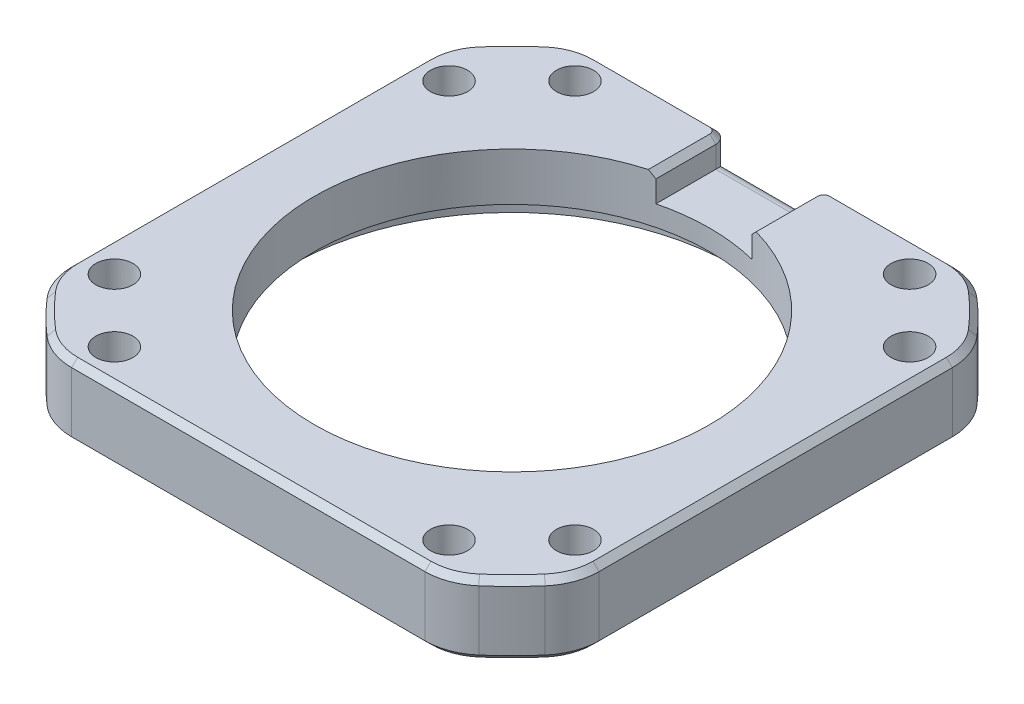
SolidWorks part; units mm, degrees
material "6061 合金"
ref_plane "前视基准面" through (0, 0, 0) normal (0, 0, 1) x (1, 0, 0)
ref_plane "上视基准面" through (0, 0, 0) normal (0, 1, 0) x (1, 0, 0)
ref_plane "右视基准面" through (0, 0, 0) normal (1, 0, 0) x (0, 0, -1)
sketch "草图1" plane through (0, 0, 0) normal (0, 1, 0) x (1, 0, 0)
  line L0 (-16.5, 22) -> (16.5, 22)
  line L1 (-22, 16.5) -> (-22, -16.5)
  line L2 (-16.5, -22) -> (16.5, -22)
  line L3 (22, 16.5) -> (22, -16.5)
  arc A24 (-16.5, 22) -> (-22, 16.5) centre (0, 0) ccw
  arc A25 (22, 16.5) -> (16.5, 22) centre (0, 0) ccw
  arc A26 (16.5, -22) -> (22, -16.5) centre (0, 0) ccw
  arc A27 (-22, -16.5) -> (-16.5, -22) centre (0, 0) ccw
  dimension "D1" = 55
  dimension "D2" = 22
  dimension "D3" = 22
  dimension "D4" = 22
  dimension "D5" = 22
extrude "凸台-拉伸1" add sketch "草图1" along normal blind 6
sketch "草图2" plane through (0, 6, 0) normal (0, 1, 0) x (1, 0, 0)
  circle A0 centre (0, 0) radius 10.5
  dimension "D1" = 21
extrude "切除-拉伸1" cut sketch "草图2" against normal blind 10
sketch "草图3" plane through (0, 6, 0) normal (0, 1, 0) x (1, 0, 0)
  line L0 (-19.2142, 13.9599) -> (0, 0) construction
  line L1 (0, 0) -> (-23.75, 0) construction
  line L2 (0, 0) -> (-16.7938, 16.7938) construction
  line L3 (0, 23.75) -> (0, 0) construction
  circle A0 centre (0, 0) radius 23.75 construction
  circle A1 centre (-19.2142, 13.9599) radius 1.55
  circle A2 centre (-13.9599, 19.2142) radius 1.55
  circle A3 centre (19.2142, 13.9599) radius 1.55
  circle A4 centre (13.9599, 19.2142) radius 1.55
  circle A5 centre (19.2142, -13.9599) radius 1.55
  circle A6 centre (13.9599, -19.2142) radius 1.55
  circle A7 centre (-19.2142, -13.9599) radius 1.55
  circle A8 centre (-13.9599, -19.2142) radius 1.55
  dimension "D1" = 47.5
  dimension "D3" = 3.1
  dimension "D2" = 36
  dimension "D4" = 45
extrude "切除-拉伸2" cut sketch "草图3" against normal blind 10
sketch "草图4" plane through (0, 6, 0) normal (0, 1, 0) x (1, 0, 0)
  circle B0 centre (18.6877, 26.5899) radius 1.55
  circle B1 centre (26.5899, 18.6877) radius 1.55
  circle B2 centre (26.5899, -18.6877) radius 1.55
  circle B3 centre (18.6877, -26.5899) radius 1.55
  circle B4 centre (-18.6877, -26.5899) radius 1.55
  circle B5 centre (-26.5899, -18.6877) radius 1.55
  circle B6 centre (-26.5899, 18.6877) radius 1.55
  circle B7 centre (-18.6877, 26.5899) radius 1.55
  arc B8 (-29.742, 3.9261) -> (-29.742, -3.9261) centre (0, 0) ccw
  arc B9 (-29.9601, -18.4937) -> (-29.742, -3.9261) centre (-79.312, -10.4695) ccw
  arc B10 (-29.9601, -18.4937) -> (-29.4534, -20.7002) centre (-26.9989, -18.9752) ccw
  arc B11 (-29.4534, -20.7002) -> (-20.7002, -29.4534) centre (0, 0) ccw
  arc B12 (-20.7002, -29.4534) -> (-18.4937, -29.9601) centre (-18.9752, -26.9989) ccw
  arc B13 (-3.9261, -29.742) -> (-18.4937, -29.9601) centre (-10.4695, -79.312) ccw
  arc B14 (-3.9261, -29.742) -> (3.9261, -29.742) centre (0, 0) ccw
  arc B15 (18.4937, -29.9601) -> (3.9261, -29.742) centre (10.4695, -79.312) ccw
  arc B16 (18.4937, -29.9601) -> (20.7002, -29.4534) centre (18.9752, -26.9989) ccw
  arc B17 (20.7002, -29.4534) -> (29.4534, -20.7002) centre (0, 0) ccw
  arc B18 (29.4534, -20.7002) -> (29.9601, -18.4937) centre (26.9989, -18.9752) ccw
  arc B19 (29.742, -3.9261) -> (29.9601, -18.4937) centre (79.312, -10.4695) ccw
  arc B20 (29.742, -3.9261) -> (29.742, 3.9261) centre (0, 0) ccw
  arc B21 (29.9601, 18.4937) -> (29.742, 3.9261) centre (79.312, 10.4695) ccw
  arc B22 (29.9601, 18.4937) -> (29.4534, 20.7002) centre (26.9989, 18.9752) ccw
  arc B23 (29.4534, 20.7002) -> (20.7002, 29.4534) centre (0, 0) ccw
  arc B24 (20.7002, 29.4534) -> (18.4937, 29.9601) centre (18.9752, 26.9989) ccw
  arc B25 (3.9261, 29.742) -> (18.4937, 29.9601) centre (10.4695, 79.312) ccw
  arc B26 (3.9261, 29.742) -> (-3.9261, 29.742) centre (0, 0) ccw
  arc B27 (-18.4937, 29.9601) -> (-3.9261, 29.742) centre (-10.4695, 79.312) ccw
  arc B28 (-18.4937, 29.9601) -> (-20.7002, 29.4534) centre (-18.9752, 26.9989) ccw
  arc B29 (-20.7002, 29.4534) -> (-29.4534, 20.7002) centre (0, 0) ccw
  arc B30 (-29.4534, 20.7002) -> (-29.9601, 18.4937) centre (-26.9989, 18.9752) ccw
  arc B31 (-29.742, 3.9261) -> (-29.9601, 18.4937) centre (-79.312, 10.4695) ccw
sketch_block_instance "块2-1"
sketch_block "块2"
sketch "草图7" plane through (0, 6, 0) normal (0, 1, 0) x (1, 0, 0)
  line L0 (0, 0) -> (0, 22) construction
  line L1 (0, 0) -> (22, 0) construction
  line L2 (-8, 48.931) -> (8, 48.931)
  line L3 (-8, 48.931) -> (-8, 4.0988)
  line L4 (-8, 4.0988) -> (8, 4.0988)
  line L5 (8, 48.931) -> (8, 4.0988)
  line L6 (16.5, 22) -> (-16.5, 22) construction
  line L7 (22, -16.5) -> (22, 16.5) construction
  dimension "D1" = 8
  dimension "D2" = 4.0988
  dimension "D3" = 8
extrude "切除-拉伸4" cut sketch "草图7" against normal blind 10
fillet "圆角1" radius 3 2 edges at (-8, 3, -22) (8, 3, -22)
fillet "圆角2" radius 5 8 edges at (-16.5, 3, 22) (-22, 3, 16.5) (-22, 3, -16.5) (-16.5, 3, -22) (16.5, 3, 22) (22, 3, 16.5) (22, 3, -16.5) (16.5, 3, -22)
sketch "草图8" plane through (0, 0, 0) normal (0, -1, 0) x (1, 0, 0)
  line L0 (8, -6.8007) -> (8, -19) construction
  line L1 (-8, -19) -> (-8, -6.8007) construction
  line L2 (8, -6.8007) -> (8, -19)
  line L3 (-8, -19) -> (-8, -6.8007)
  line L4 (-8, -19) -> (8, -19)
  arc A0 (8, -6.8007) -> (-8, -6.8007) centre (0, 0) ccw construction
  arc A1 (8, -6.8007) -> (-8, -6.8007) centre (0, 0) ccw
extrude "凸台-拉伸2" add sketch "草图8" against normal up to surface (6 mm away) up to face at (0, 6, -3.6156)
sketch "草图9" plane through (0, 0, 0) normal (0, -1, 0) x (1, 0, 0)
  circle A0 centre (0, 0) radius 9.75
  dimension "D1" = 19.5
extrude "切除-拉伸5" cut sketch "草图9" against normal through all
sketch "草图10" plane through (0, 0, 0) normal (0, -1, 0) x (1, 0, 0)
  circle A0 centre (0, 0) radius 13
  dimension "D1" = 26
extrude "切除-拉伸6" cut sketch "草图10" against normal blind 2
sketch "草图11" plane through (0, 6, 0) normal (0, 1, 0) x (1, 0, 0)
  line L0 (0, 0) -> (0, 25.074) construction
  line L2 (-4, 24.8917) -> (4, 24.8917)
  line L3 (-4, 24.8917) -> (-4, 8.8917)
  line L4 (-4, 8.8917) -> (4, 8.8917)
  line L5 (4, 24.8917) -> (4, 8.8917)
  line L6 (-4, 24.8917) -> (4, 8.8917) construction
  line L7 (-4, 8.8917) -> (4, 24.8917) construction
  circle A0 centre (0, 0) radius 9.75 construction
  point P2 (0, 16.8917)
  dimension "D1" = 8
  dimension "D2" = 16
extrude "切除-拉伸7" cut sketch "草图11" against normal blind 2.3
fillet "圆角3" radius 1 3 edges at (0, 3.7, -9.75) (-4, 4.85, -8.8917) (4, 4.85, -8.8917)
sketch "草图12" plane through (0, 0, 0) normal (0, -1, 0) x (1, 0, 0)
  line L0 (-8, -19) -> (8, -19) construction
  line L1 (-8, -19) -> (8, -19)
  line L2 (-11, -22) -> (11, -22)
  arc A0 (8, -19) -> (11, -22) centre (11, -19) ccw construction
  arc A1 (-11, -22) -> (-8, -19) centre (-11, -19) ccw construction
  arc A2 (8, -19) -> (11, -22) centre (11, -19) ccw
  arc A3 (-11, -22) -> (-8, -19) centre (-11, -19) ccw
  line M2 (-8, -19) -> (8, -19)
  arc M3 (8, -19) -> (11, -22) centre (11, -19) ccw
  arc M21 (-11, -22) -> (-8, -19) centre (-11, -19) ccw
extrude "凸台-拉伸3" add sketch "草图12" against normal up to surface (6 mm away) contours L2 M21 M3 M2 up to face at (0, 6, -5.3464)
sketch "草图13" plane through (0, 6, 0) normal (0, 1, 0) x (1, 0, 0)
  line L0 (0, 0) -> (0, 24.0923) construction
  line L1 (-4, 19) -> (-4, 22)
  line L2 (14.7394, 22) -> (-14.7394, 22) construction
  line L3 (-4, 22) -> (4, 22)
  line L4 (4, 22) -> (4, 19)
  line L5 (4, 19) -> (-4, 19)
extrude "切除-拉伸8" cut sketch "草图13" against normal blind 2.3
fillet "圆角4" radius 1 3 edges at (-4, 4.85, -22) (4, 4.85, -22) (0, 3.7, -22)
chamfer "倒角1" distance 0.5 angle 45 40 edges at (0, 0, 22) (0, 6, 22) (16.4874, 6, 21.6845) (16.4874, 0, 21.6845) (-16.4874, 6, 21.6845) (-16.4874, 0, 21.6845) (19.4454, 6, 19.4454) (19.4454, 0, 19.4454) (-19.4454, 0, 19.4454) (-19.4454, 6, 19.4454) (21.6845, 6, 16.4874) (21.6845, 0, 16.4874) (-21.6845, 6, 16.4874) (-21.6845, 0, 16.4874) (22, 6, 0) (22, 0, 0) (-22, 0, 0) (-22, 6, 0) (21.6845, 6, -16.4874) (21.6845, 0, -16.4874) (-21.6845, 6, -16.4874) (-21.6845, 0, -16.4874) (19.4454, 6, -19.4454) (19.4454, 0, -19.4454) (-19.4454, 0, -19.4454) (-19.4454, 6, -19.4454) (16.4874, 6, -21.6845) (16.4874, 0, -21.6845) (-16.4874, 6, -21.6845) (-16.4874, 0, -21.6845) (0, 0, -22) (-9.8697, 6, -22) (-4.2929, 6, -21.7071) (-4, 6, -15.2582) (-4.1441, 6, -8.9993) (0, 6, 9.75) (4.1441, 6, -8.9993) (4, 6, -15.2582) (4.2929, 6, -21.7071) (9.8697, 6, -22)
sketch "草图14" plane through (0, 0, 0) normal (0, -1, 0) x (1, 0, 0)
  circle A0 centre (0, 0) radius 13 construction
  circle A1 centre (0, 0) radius 13
  circle A2 centre (0, 0) radius 15
  dimension "D1" = 30
extrude "凸台-拉伸4" add sketch "草图14" along normal blind 3
chamfer "倒角2" distance 0.5 angle 45 2 edges at (0, -3, -13) (0, -3, -15)
sketch "草图15" plane through (0, 0, 0) normal (0, -1, 0) x (1, 0, 0)
  circle A0 centre (0, 0) radius 17.0007
extrude "切除-拉伸9" cut sketch "草图15" along normal blind 23
sketch "草图17" plane through (0, 0, 0) normal (0, -1, 0) x (1, 0, 0)
  circle A0 centre (0, 0) radius 18.5
  dimension "D1" = 37
extrude "切除-拉伸11" cut sketch "草图17" against normal up to surface (2 mm away) contours A0 up to face at (0, 2, -13)
sketch "草图18" plane through (0, 2, 0) normal (0, -1, 0) x (1, 0, 0)
  circle A0 centre (0, 0) radius 16.5
  dimension "D1" = 33
extrude "切除-拉伸12" cut sketch "草图18" against normal blind 14
